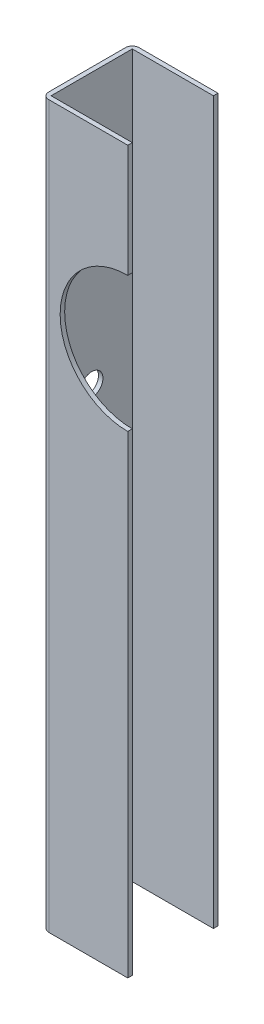
SolidWorks part; units mm, degrees
ref_plane "Front Plane" through (0, 0, 0) normal (0, 0, 1) x (1, 0, 0)
ref_plane "Top Plane" through (0, 0, 0) normal (0, 1, 0) x (1, 0, 0)
ref_plane "Right Plane" through (0, 0, 0) normal (1, 0, 0) x (0, 0, -1)
sketch "Sketch1" plane through (0, 0, 0) normal (0, 1, 0) x (1, 0, 0)
  line L1 (-12.7, -12.7) -> (12.7, -12.7)
  line L2 (-12.7, -12.7) -> (-12.7, 12.7)
  line L3 (-12.7, 12.7) -> (12.7, 12.7)
  line L4 (12.7, -12.7) -> (12.7, 12.7)
  line L5 (-12.7, -12.7) -> (12.7, 12.7) construction
  line L6 (-12.7, 12.7) -> (12.7, -12.7) construction
  line L7 (-11.43, -11.43) -> (11.43, -11.43)
  line L8 (-11.43, -11.43) -> (-11.43, 11.43)
  line L9 (-11.43, 11.43) -> (11.43, 11.43)
  line L10 (11.43, -11.43) -> (11.43, 11.43)
  line L11 (-11.43, -11.43) -> (11.43, 11.43) construction
  line L12 (-11.43, 11.43) -> (11.43, -11.43) construction
  point P0 (0, 0)
  point P6 (0, 0)
  point P11 (-56.9643, 20.4611)
  point P12 (-60.0836, 22.6892)
  dimension "D1" = 25.4
  dimension "D2" = 25.4
  dimension "D3" = 22.86
extrude "Boss-Extrude1" add sketch "Sketch1" along normal blind 203.2
sketch "Sketch2" plane through (12.7, 0, 0) normal (1, 0, 0) x (0, 0, -1)
  line L1 (-12.7, 203.2) -> (12.7, 203.2)
  line L2 (-12.7, 203.2) -> (-12.7, 0)
  line L3 (-12.7, 0) -> (12.7, 0)
  line L4 (12.7, 203.2) -> (12.7, 0)
extrude "Cut-Extrude1" cut sketch "Sketch2" against normal up to surface (1.27 mm away) up to face at (11.43, 101.6, 0)
sketch "Sketch3" plane through (-12.7, 0, 0) normal (-1, 0, 0) x (0, 0, 1)
  line L1 (0, 25.4) -> (0, 76.2) construction
  line L2 (-12.7, 0) -> (12.7, 0) construction
  line L3 (-12.7, 203.2) -> (12.7, 203.2) construction
  circle A0 centre (0, 25.4) radius 3.175
  circle A1 centre (0, 76.2) radius 3.175
  circle A2 centre (0, 127) radius 3.175
  circle A3 centre (0, 177.8) radius 3.175
  point P14 (-2.1153, 153.5914)
  point P15 (-29.051, -74.3841)
  point P16 (0, 0)
  dimension "D1" = 6.35
  dimension "D4" = 25.4
  dimension "D5" = 25.4
  dimension "D3" = 50.8
  dimension "D2" = 4
sketch "Sketch4" plane through (0, 0, 12.7) normal (0, 0, 1) x (1, 0, 0)
  line L1 (11.43, 203.2) -> (11.43, 0) construction
  line L2 (-12.7, 203.2) -> (11.43, 203.2) construction
  arc A1 (11.43, 171.45) -> (11.43, 133.35) centre (11.43, 152.4) ccw
  point P5 (11.43, 195.7388)
  dimension "D1" = 19.05
  dimension "D2" = 50.8
extrude "Cut-Extrude2" cut sketch "Sketch3" against normal up to surface (1.27 mm away) up to face at (-11.43, 101.6, 0)
extrude "Cut-Extrude3" cut sketch "Sketch4" against normal blind 2.54 and the other way through all
fillet "Fillet10" radius 1.905 2 edges at (-12.7, 101.6, -12.7) (-12.7, 101.6, 12.7)
equation "\"mount_length\"= 8"
equation "\"mount_height\"= 1"
equation "\"mount_width\"= 1"
equation "\"D1@Sketch1\"=\"mount_height\""
equation "\"D2@Sketch1\"=\"mount_width\""
equation "\"D3@Sketch1\"=\"mount_width\"-.1"
equation "\"D1@Boss-Extrude1\"=\"mount_length\""
equation "\"edge_dist\"= 1"
equation "\"D5@Sketch3\"=\"edge_dist\""
equation "\"D4@Sketch3\"=\"edge_dist\""
equation "\"hose_rad\"= .75"
equation "\"D1@Sketch4\"=\"hose_rad\""
